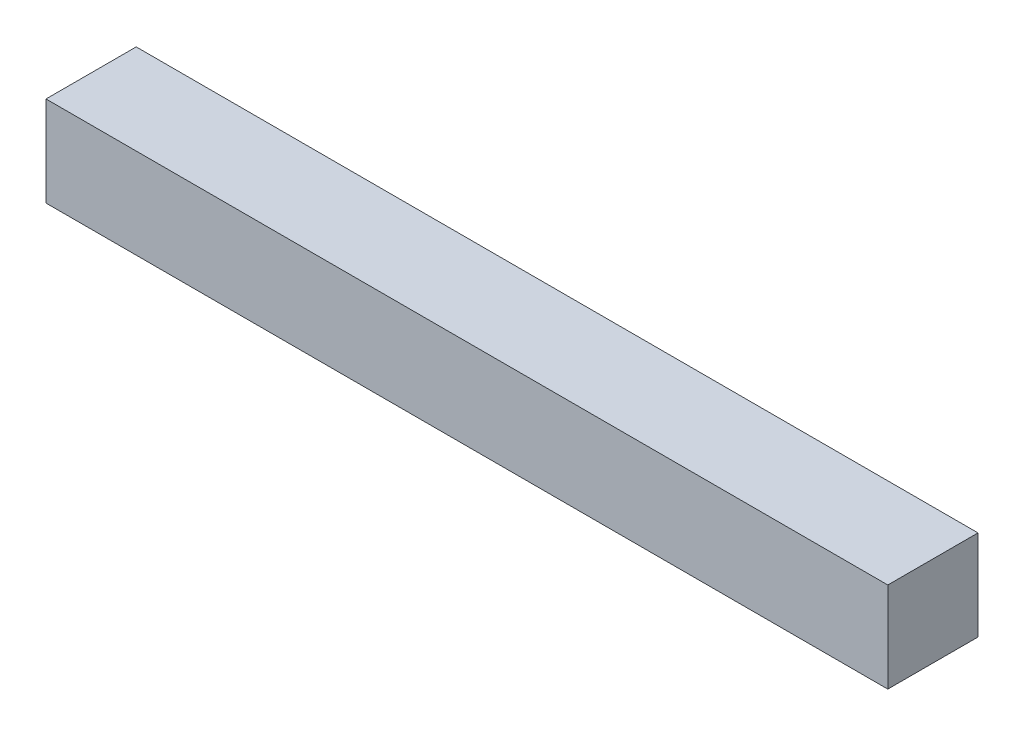
SolidWorks part; units mm, degrees
ref_plane "Front Plane" through (0, 0, 0) normal (0, 0, 1) x (1, 0, 0)
ref_plane "Top Plane" through (0, 0, 0) normal (0, 1, 0) x (1, 0, 0)
ref_plane "Right Plane" through (0, 0, 0) normal (1, 0, 0) x (0, 0, -1)
other "Configuration Table"
sketch "Sketch1" plane through (0, 0, 0) normal (0, 0, 1) x (1, 0, 0)
  line L1 (-70, 245) -> (70, 245)
  line L2 (-70, 245) -> (-70, 260)
  line L3 (-70, 260) -> (70, 260)
  line L4 (70, 245) -> (70, 260)
extrude "KAP_on_cekme_dudagi_1" add sketch "Sketch1" against normal blind 15 from offset 5 separate body
